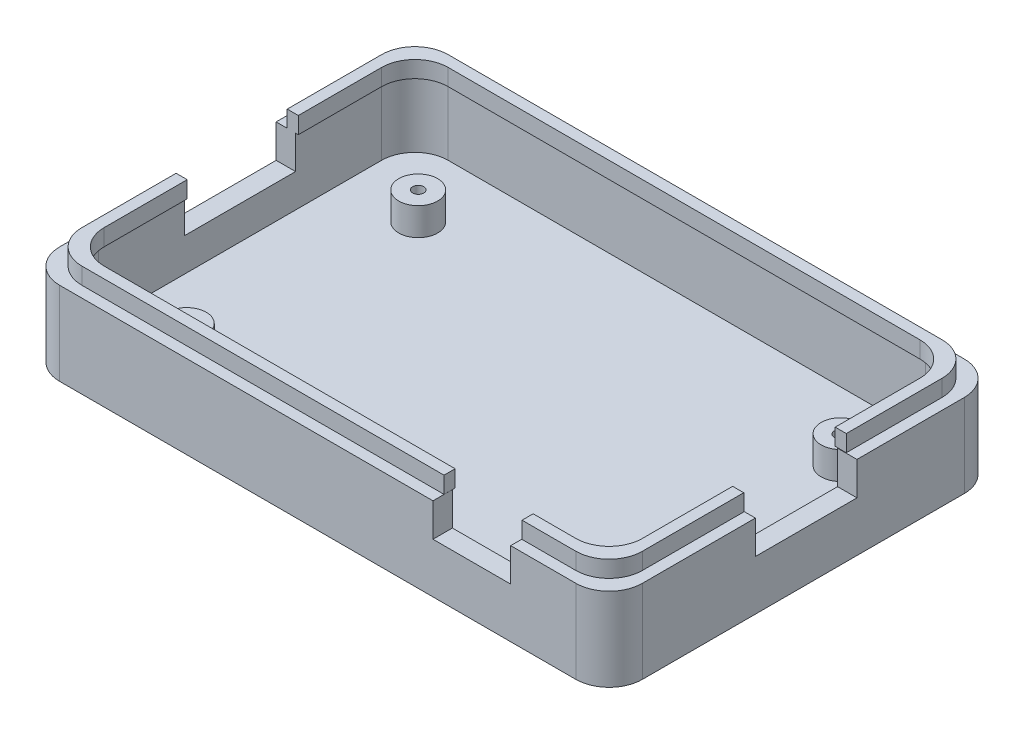
SolidWorks part; units mm, degrees
ref_plane "Front Plane" through (0, 0, 0) normal (0, 0, 1) x (1, 0, 0)
ref_plane "Top Plane" through (0, 0, 0) normal (0, 1, 0) x (1, 0, 0)
ref_plane "Right Plane" through (0, 0, 0) normal (1, 0, 0) x (0, 0, -1)
sketch "Sketch1" plane through (0, 0, 0) normal (0, 1, 0) x (1, 0, 0)
  line L1 (-52.5, 35) -> (52.5, 35)
  line L2 (-52.5, 35) -> (-52.5, -35)
  line L3 (-52.5, -35) -> (52.5, -35)
  line L4 (52.5, 35) -> (52.5, -35)
  line L5 (-52.5, 35) -> (52.5, -35) construction
  line L6 (-52.5, -35) -> (52.5, 35) construction
  point P0 (0, 0)
  dimension "D1" = 105
  dimension "D2" = 70
extrude "Boss-Extrude1" add sketch "Sketch1" along normal blind 15
sketch "Sketch3" plane through (0, 15, 0) normal (0, 1, 0) x (1, 0, 0)
  line L0 (52.5, -35) -> (52.5, 35) construction
  line L1 (49, -31.5) -> (-49, -31.5)
  line L2 (49, -31.5) -> (49, 31.5)
  line L3 (49, 31.5) -> (-49, 31.5)
  line L4 (-49, -31.5) -> (-49, 31.5)
  line L5 (49, -31.5) -> (-49, 31.5) construction
  line L6 (49, 31.5) -> (-49, -31.5) construction
  line L7 (-52.5, -35) -> (52.5, -35) construction
  point P0 (0, 0)
  dimension "D1" = 3.5
  dimension "D2" = 3.5
extrude "Cut-Extrude1" cut sketch "Sketch3" against normal blind 12
fillet "Fillet1" radius 6 8 edges at (-52.5, 7.5, -35) (-52.5, 7.5, 35) (52.5, 7.5, -35) (52.5, 7.5, 35) (49, 9, -31.5) (-49, 9, -31.5) (-49, 9, 31.5) (49, 9, 31.5)
sketch "Sketch4" plane through (0, 3, 0) normal (0, 1, 0) x (1, 0, 0)
  line L0 (-43, -31.5) -> (43, -31.5) construction
  line L1 (49, -25.5) -> (49, 25.5) construction
  circle A0 centre (40, -22.5) radius 3.5
  circle A1 centre (40, 19.2) radius 3.5
  circle A2 centre (-36.1, -22.5) radius 3.5
  circle A3 centre (-36.1, 19.2) radius 3.5
  dimension "D5" = 7
  dimension "D6" = 76.1
  dimension "D1" = 41.7
  dimension "D2" = 9
  dimension "D3" = 76.1
  dimension "D4" = 9
  dimension "D7" = 41.7
extrude "Boss-Extrude2" add sketch "Sketch4" along normal blind 5
sketch "Sketch5" plane through (0, 8, 0) normal (0, 1, 0) x (1, 0, 0)
  circle A0 centre (-36.1, 19.2) radius 1
  circle A1 centre (-36.1, -22.5) radius 1
  circle A2 centre (40, -22.5) radius 1
  circle A3 centre (40, 19.0603) radius 1
  dimension "D1" = 2
extrude "Cut-Extrude2" cut sketch "Sketch5" against normal blind 8
sketch "Sketch6" plane through (0, 15, 0) normal (0, 1, 0) x (1, 0, 0)
  line L0 (49, -25.5) -> (49, 25.5) construction
  line L1 (49, 9.66) -> (52.5, 9.66)
  line L2 (49, 9.66) -> (49, -8.64)
  line L3 (49, -8.64) -> (52.5, -8.64)
  line L4 (52.5, 9.66) -> (52.5, -8.64)
  line L5 (52.5, -29) -> (52.5, 29) construction
  line L6 (-46.5, -35) -> (46.5, -35) construction
  line L7 (34.76, -35) -> (20.76, -35)
  line L8 (34.76, -35) -> (34.76, -31.5)
  line L9 (34.76, -31.5) -> (20.76, -31.5)
  line L10 (20.76, -35) -> (20.76, -31.5)
  line L11 (-43, -31.5) -> (43, -31.5) construction
  line L12 (-52.5, 29) -> (-52.5, -29) construction
  line L13 (-52.5, 10) -> (-49, 10)
  line L14 (-52.5, 10) -> (-52.5, -10)
  line L15 (-52.5, -10) -> (-49, -10)
  line L16 (-49, 10) -> (-49, -10)
  line L17 (-49, 25.5) -> (-49, -25.5) construction
  dimension "D1" = 14
  dimension "D2" = 20
  dimension "D3" = 25
  dimension "D4" = 14.24
  dimension "D5" = 22.86
  dimension "D6" = 18.3
extrude "Cut-Extrude3" cut sketch "Sketch6" against normal blind 6
sketch "Sketch7" plane through (0, 15, 0) normal (0, 1, 0) x (1, 0, 0)
  line L0 (0, 35) -> (0, -35) construction
  line L1 (46.5, 35) -> (-46.5, 35) construction
  line L2 (-46.5, -35) -> (20.76, -35) construction
  line L3 (-52.5, -10) -> (-52.5, -29) construction
  line L4 (-44.5, 33) -> (44.5, 33)
  line L5 (-50.5, 27) -> (-50.5, 10)
  line L6 (-44.5, -33) -> (20.7545, -33)
  line L7 (50.5, 27) -> (50.5, 9.7366)
  line L8 (-50.5, 33) -> (50.5, -33) construction
  line L9 (-50.5, -33) -> (50.5, 33) construction
  line L10 (50.5, -8.7396) -> (50.5, -27)
  line L11 (-42.5, 31) -> (42.5, 31)
  line L12 (-48.5, 25) -> (-48.5, 10)
  line L13 (-42.5, -31) -> (20.7545, -31)
  line L14 (48.5, 25) -> (48.5, 9.7366)
  line L15 (-48.5, 31) -> (48.5, -31) construction
  line L16 (-48.5, -31) -> (48.5, 31) construction
  line L17 (50.5, 9.7366) -> (48.5, 9.7366)
  line L19 (50.5, -8.7396) -> (48.5, -8.7396)
  line L20 (-50.5, 10) -> (-48.5, 10)
  line L21 (48.5, -8.7396) -> (48.5, -25)
  line L22 (34.8092, -31) -> (42.5, -31)
  line L23 (-50.5, -10.027) -> (-48.5, -10.027)
  line L25 (-48.5, -10.027) -> (-48.5, -25)
  line L26 (-50.5, -10.027) -> (-50.5, -27)
  line L27 (34.8092, -33) -> (34.8092, -31)
  line L29 (20.7545, -33) -> (20.7545, -31)
  line L30 (34.8092, -33) -> (44.5, -33)
  arc A0 (44.5, 33) -> (50.5, 27) centre (44.5, 27) cw
  arc A1 (-44.5, 33) -> (-50.5, 27) centre (-44.5, 27) ccw
  arc A2 (44.5, -33) -> (50.5, -27) centre (44.5, -27) ccw
  arc A3 (-50.5, -27) -> (-44.5, -33) centre (-44.5, -27) ccw
  arc A4 (-42.5, 31) -> (-48.5, 25) centre (-42.5, 25) ccw
  arc A5 (-48.5, -25) -> (-42.5, -31) centre (-42.5, -25) ccw
  arc A6 (42.5, -31) -> (48.5, -25) centre (42.5, -25) ccw
  arc A7 (42.5, 31) -> (48.5, 25) centre (42.5, 25) cw
  point P7 (0, 0)
  point P26 (0, 0)
  dimension "D3" = 6
  dimension "D6" = 6
  dimension "D1" = 2
  dimension "D2" = 2
  dimension "D4" = 2
  dimension "D5" = 2
extrude "Boss-Extrude3" add sketch "Sketch7" along normal blind 3
equation "\"D2@Sketch3\"=\"D1@Sketch3\""
equation "\"D4@Sketch4\"=\"D2@Sketch4\""
equation "\"D6@Sketch4\"=\"D3@Sketch4\""
equation "\"D7@Sketch4\"=\"D1@Sketch4\""
